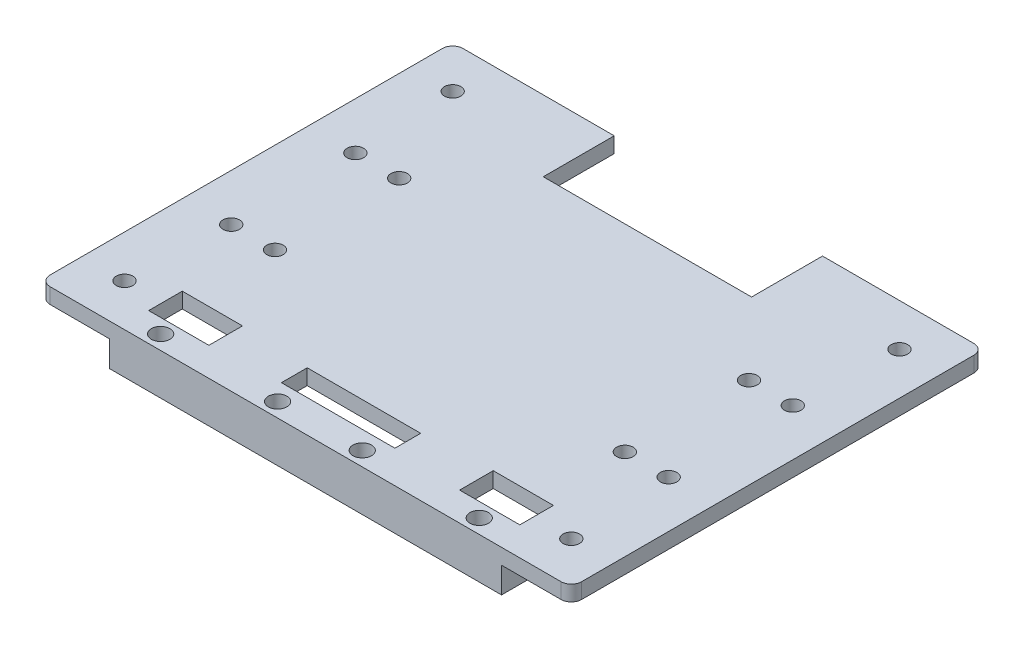
SolidWorks part; units mm, degrees
ref_plane "前视基准面" through (0, 0, 0) normal (0, 0, 1) x (1, 0, 0)
ref_plane "上视基准面" through (0, 0, 0) normal (0, 1, 0) x (1, 0, 0)
ref_plane "右视基准面" through (0, 0, 0) normal (1, 0, 0) x (0, 0, -1)
sketch "草图1" plane through (0, 0, 0) normal (0, 1, 0) x (1, 0, 0)
  line L0 (-51.5, 40) -> (-43.3, 31.8) construction
  line L1 (49.5, -40) -> (-49.5, -40)
  line L2 (51.5, -38) -> (51.5, 38)
  line L3 (49.5, 40) -> (-49.5, 40)
  line L4 (-51.5, -38) -> (-51.5, 38)
  line L5 (51.5, -40) -> (-51.5, 40) construction
  line L6 (51.5, 40) -> (-51.5, -40) construction
  line L7 (20.1874, 26.2491) -> (-20.1874, 26.2491)
  line L8 (20.1874, 26.2491) -> (20.1874, 36.5704)
  line L10 (-20.1874, 26.2491) -> (-20.1874, 36.5704)
  line L11 (20.1874, 26.2491) -> (-20.1874, 36.5704) construction
  line L12 (20.1874, 36.5704) -> (-20.1874, 26.2491) construction
  line L13 (0, 31.4098) -> (0, -40) construction
  line L14 (51.5, 0) -> (-51.5, 0)
  line L16 (11, -33.6959) -> (-11, -33.6959)
  line L17 (11, -33.6959) -> (11, -28.6959)
  line L18 (11, -28.6959) -> (-11, -28.6959)
  line L19 (-11, -33.6959) -> (-11, -28.6959)
  line L20 (11, -33.6959) -> (-11, -28.6959) construction
  line L21 (11, -28.6959) -> (-11, -33.6959) construction
  line L26 (24.3014, -27.9372) -> (35.9691, -27.9372)
  line L27 (-24.3014, -34.4545) -> (-35.9691, -34.4545)
  line L31 (-24.3014, -34.4545) -> (-24.3014, -27.9372)
  line L32 (-24.3014, -27.9372) -> (-35.9691, -27.9372)
  line L33 (-35.9691, -34.4545) -> (-35.9691, -27.9372)
  line L34 (-24.3014, -34.4545) -> (-35.9691, -27.9372) construction
  line L35 (-24.3014, -27.9372) -> (-35.9691, -34.4545) construction
  line L36 (35.9691, -34.4545) -> (35.9691, -27.9372)
  line L37 (24.3014, -34.4545) -> (35.9691, -34.4545)
  line L38 (24.3014, -34.4545) -> (24.3014, -27.9372)
  line L39 (-43.3, 31.8) -> (-43.3, -31.8) construction
  line L47 (-38.1468, 18.3) -> (-38.1468, -18.3) construction
  line L48 (-38.1468, 18.3) -> (-38.1468, 12.03)
  line L49 (-33.9018, 12.03) -> (-42.3918, 12.03)
  line L50 (-20.1874, 36.5704) -> (-20.1874, 40)
  line L51 (-20.1874, 40) -> (20.1874, 40)
  line L52 (20.1874, 40) -> (20.1874, 36.5704)
  circle A0 centre (-43.3, 31.8) radius 1.6
  circle A1 centre (43.3, 31.8) radius 1.6
  circle A2 centre (43.3, -31.8) radius 1.6
  circle A3 centre (-43.3, -31.8) radius 1.6
  arc A4 (-49.5, -40) -> (-51.5, -38) centre (-49.5, -38) cw
  arc A5 (49.5, -40) -> (51.5, -38) centre (49.5, -38) ccw
  arc A6 (51.5, 38) -> (49.5, 40) centre (49.5, 38) ccw
  arc A7 (-49.5, 40) -> (-51.5, 38) centre (-49.5, 38) ccw
  circle A8 centre (-42.3918, 12.03) radius 1.6
  circle A9 centre (-33.9018, 12.03) radius 1.6
  circle A10 centre (-33.9018, -12.03) radius 1.6
  circle A11 centre (-42.3918, -12.03) radius 1.6
  circle A12 centre (33.9018, -12.03) radius 1.6
  circle A13 centre (42.3918, -12.03) radius 1.6
  circle A14 centre (33.9018, 12.03) radius 1.6
  circle A15 centre (42.3918, 12.03) radius 1.6
  point P0 (0, 0)
  point P6 (0, 31.4098)
  point P18 (0, 0)
  point P36 (0, -31.1959)
  point P41 (-69.6672, -54.1104)
  point P42 (-30.1353, -31.1959)
  point P54 (-43.3, 0)
  point P62 (-38.1468, 12.03)
  dimension "D4" = 2
  dimension "D5" = 86.6
  dimension "D1" = 103
  dimension "D2" = 80
  dimension "D3" = 45
  dimension "D6" = 63.6
extrude "凸台-拉伸1" add sketch "草图1" along normal blind 3
ref_plane "基准面1" through (0, 3, 0) normal (0, 1, 0) x (1, 0, 0)
sketch "草图2" plane through (0, 3, 0) normal (0, 1, 0) x (1, 0, 0)
  line L0 (49.5, -40) -> (-49.5, -40) construction
  line L1 (-37.9691, -34.4545) -> (37.9691, -34.4545)
  line L2 (-37.9691, -34.4545) -> (-37.9691, -40)
  line L3 (-37.9691, -40) -> (37.9691, -40)
  line L4 (37.9691, -34.4545) -> (37.9691, -40)
  line L5 (0, -34.4545) -> (0, -40) construction
  point P13 (0, -37.2273)
  point P16 (0, -37.2273)
  dimension "D1" = 2
  dimension "D2" = 2
extrude "凸台-拉伸2" add sketch "草图2" against normal blind 8
ref_plane "基准面2" through (0, -5, 0) normal (0, -1, 0) x (-1, 0, 0)
sketch "草图3" plane through (0, -5, 0) normal (0, -1, 0) x (-1, 0, 0)
  line L0 (0, -40) -> (0, -34.4545) construction
  line L1 (37.9691, -40) -> (-37.9691, -40) construction
  line L2 (-37.9691, -34.4545) -> (37.9691, -34.4545) construction
  line L3 (15, -37.2273) -> (-15, -37.2273)
  line L4 (10, -37.2273) -> (-10, -37.2273)
  circle A0 centre (-8.2, -37.2273) radius 1.8
  circle A1 centre (8.2, -37.2273) radius 1.8
  circle A2 centre (-30.8751, -37.2273) radius 1.8
  circle A3 centre (30.8751, -37.2273) radius 1.8
  point P9 (0, -37.2273)
  point P12 (0, -37.2273)
  dimension "D1" = 20
extrude "切除-拉伸1" cut sketch "草图3" against normal blind 15 contours A3 | L3 A1 | L3 A1 | L4 A0 | A2
sketch "草图4" plane through (0, 3, 0) normal (0, 1, 0) x (1, 0, 0)
  line L1 (-43.9918, 12.03) -> (-51.3273, 12.03) construction
  circle A0 centre (-42.3918, 12.03) radius 1.6 construction
